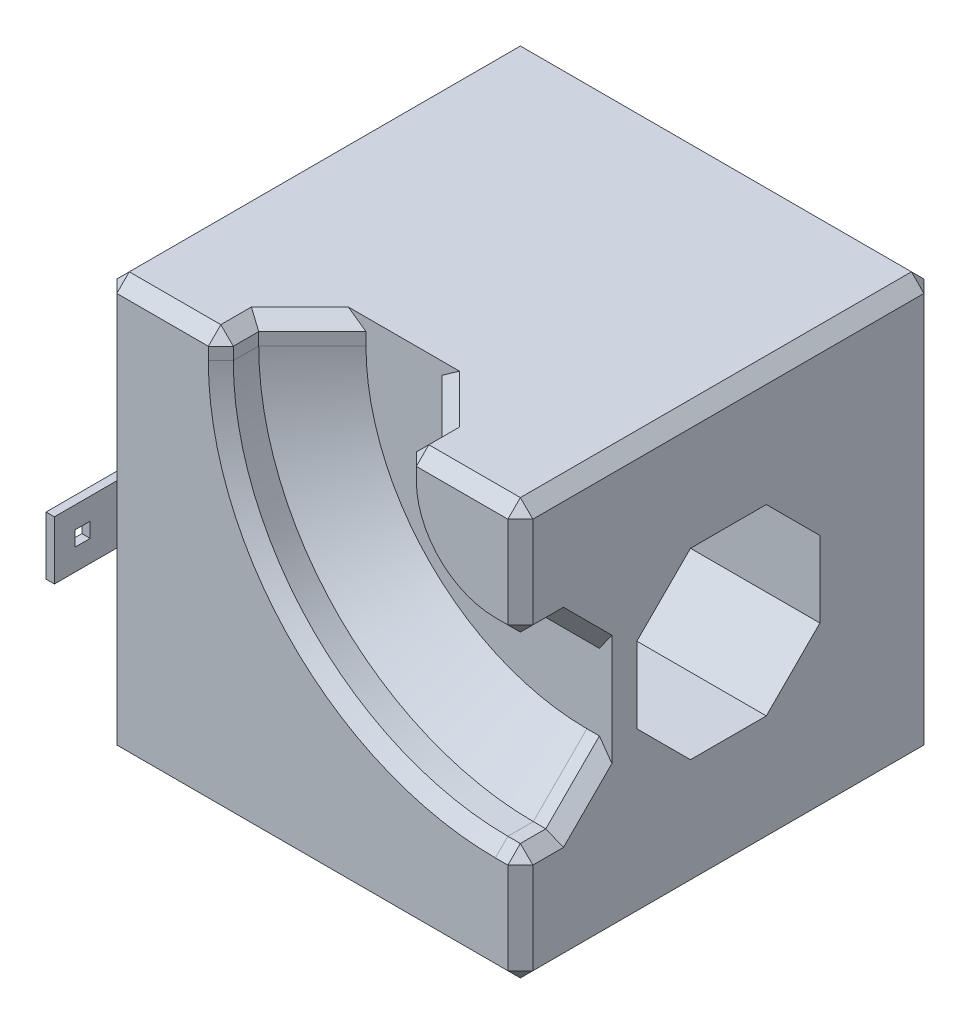
SolidWorks part; units mm, degrees
ref_plane "Front" through (0, 0, 0) normal (0, 0, 1) x (1, 0, 0)
ref_plane "Top" through (0, 0, 0) normal (0, 1, 0) x (1, 0, 0)
ref_plane "Right" through (0, 0, 0) normal (1, 0, 0) x (0, 0, -1)
sketch "Sketch1" plane through (0, 0, 0) normal (0, 0, 1) x (1, 0, 0)
  line L1 (0, 0) -> (50, 0)
  line L2 (0, 0) -> (0, 50)
  line L3 (0, 50) -> (50, 50)
  line L4 (50, 0) -> (50, 50)
  dimension "D1" = 50
extrude "Boss-Extrude1" add sketch "Sketch1" along normal blind 50
sketch "Sketch2" plane through (0, 0, 0) normal (-1, 0, 0) x (0, 0, 1)
  line L0 (25, 25) -> (25, 50) construction
  line L1 (50, 25) -> (25, 25) construction
  line L2 (50, 50) -> (50, 0) construction
  line L7 (50, 50) -> (0, 50) construction
  line L10 (14, 36) -> (36, 36) construction
  line L11 (14, 36) -> (14, 14) construction
  line L12 (14, 14) -> (36, 14) construction
  line L13 (36, 36) -> (36, 14) construction
  line L14 (36, 29.5563) -> (29.5563, 36)
  line L15 (14, 36) -> (36, 14) construction
  line L16 (29.5563, 36) -> (20.4437, 36)
  line L17 (14, 14) -> (36, 36) construction
  line L26 (20.4437, 36) -> (14, 29.5563)
  line L27 (14, 29.5563) -> (14, 20.4437)
  line L28 (14, 20.4437) -> (20.4437, 14)
  line L29 (20.4437, 14) -> (29.5563, 14)
  line L30 (29.5563, 14) -> (36, 20.4437)
  line L31 (36, 20.4437) -> (36, 29.5563)
  circle A1 centre (25, 25) radius 11 construction
  point P5 (25, 25)
  dimension "D1" = 22
extrude "Cut-Extrude1" cut sketch "Sketch2" against normal through all
sketch "Sketch3" plane through (0, 50, 0) normal (0, -1, 0) x (1, 0, 0)
  line L0 (0, 50) -> (50, 50) construction
  line L7 (14, 61) -> (36, 61) construction
  line L8 (14, 61) -> (14, 39) construction
  line L9 (14, 39) -> (36, 39) construction
  line L10 (36, 61) -> (36, 39) construction
  line L11 (14, 61) -> (36, 39) construction
  line L12 (14, 39) -> (36, 61) construction
  line L16 (29.5563, 39) -> (36, 45.4437)
  line L17 (36, 45.4437) -> (36, 54.5563)
  line L18 (36, 54.5563) -> (29.5563, 61)
  line L19 (29.5563, 61) -> (20.4437, 61)
  line L20 (20.4437, 61) -> (14, 54.5563)
  line L21 (14, 54.5563) -> (14, 45.4437)
  line L22 (14, 45.4437) -> (20.4437, 39)
  line L23 (20.4437, 39) -> (29.5563, 39)
  circle A0 centre (25, 50) radius 11 construction
  point P5 (25, 50)
  dimension "D1" = 22
sketch "Sketch4" plane through (0, 0, 50) normal (0, 0, 1) x (1, 0, 0)
  line L0 (25, 50) -> (25, 47)
  line L1 (47, 25) -> (50, 25)
  line L2 (50, 0) -> (50, 50) construction
  arc A0 (25, 47) -> (47, 25) centre (47, 47) ccw
  dimension "D1" = 22
sweep "Cut-Sweep2" cut profiles "Sketch3" path "Sketch4"
chamfer "Chamfer1" distance 1.5 angle 45 28 edges at (48.5, 14, 50) (48.5, 36, 50) (23.6655, 23.6655, 50) (39.2218, 39.2218, 50) (25, 50, 0) (0, 50, 25) (0, 25, 0) (25, 0, 0) (50, 17.2218, 42.2218) (50, 14, 47.7218) (50, 7, 50) (0, 0, 25) (14, 48.5, 50) (17.2218, 50, 42.2218) (14, 50, 47.7218) (7, 50, 50) (0, 25, 50) (25, 0, 50) (50, 0, 25) (50, 25, 0) (50, 50, 25) (36, 48.5, 50) (43, 50, 50) (50, 43, 50) (50, 32.7782, 42.2218) (50, 36, 47.7218) (32.7782, 50, 42.2218) (36, 50, 47.7218)
sketch "Sketch5" plane through (0, 0, 50) normal (0, 0, 1) x (1, 0, 0)
  line L0 (0, 1.5) -> (0, 48.5) construction
  line L1 (0, 28.5) -> (1, 28.5)
  line L2 (0, 28.5) -> (0, 21.5)
  line L3 (0, 21.5) -> (1, 21.5)
  line L4 (1, 28.5) -> (1, 21.5)
  point P6 (0, 25)
  dimension "D1" = 1
  dimension "D2" = 7
extrude "Boss-Extrude2" add sketch "Sketch5" along normal blind 7 and the other way blind 10
sketch "Sketch6" plane through (1, 0, 0) normal (1, 0, 0) x (0, 0, -1)
  line L0 (-54.5, 25) -> (-57, 25) construction
  line L1 (-54.5, 24.1) -> (-52.7, 24.1)
  line L2 (-54.5, 24.1) -> (-54.5, 25.9)
  line L3 (-54.5, 25.9) -> (-52.7, 25.9)
  line L4 (-52.7, 24.1) -> (-52.7, 25.9)
  line L5 (-57, 21.5) -> (-57, 28.5) construction
  dimension "D1" = 2.5
  dimension "D2" = 1.8
extrude "Cut-Extrude2" cut sketch "Sketch6" against normal blind 7
